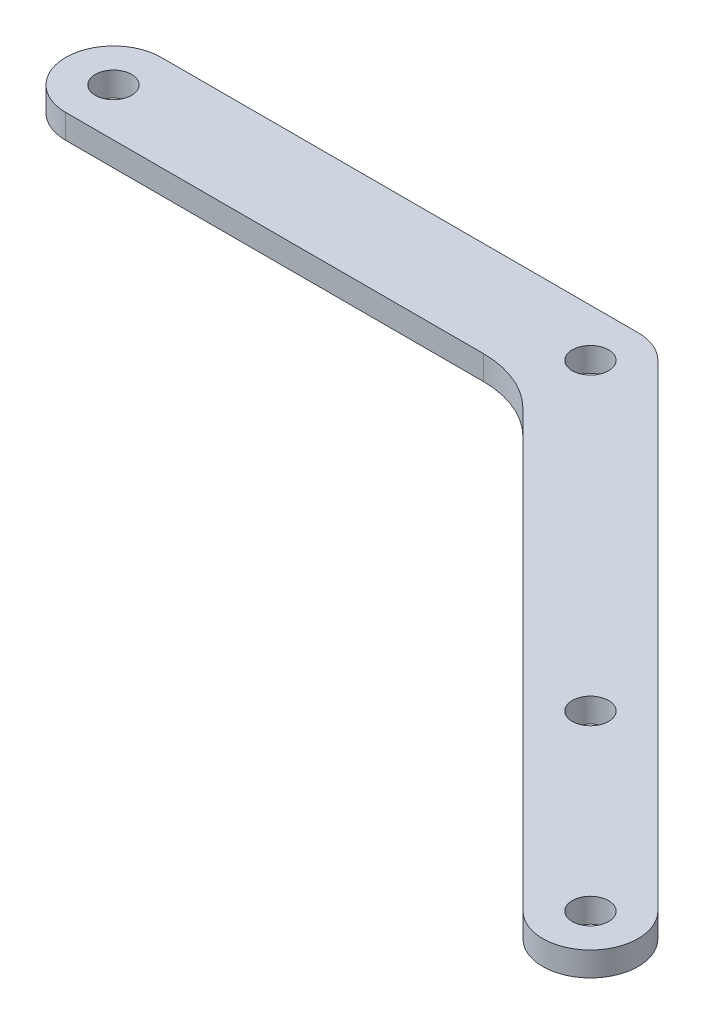
SolidWorks part; units mm, degrees
ref_plane "Front Plane" through (0, 0, 0) normal (0, 0, 1) x (1, 0, 0)
ref_plane "Top Plane" through (0, 0, 0) normal (0, 1, 0) x (1, 0, 0)
ref_plane "Right Plane" through (0, 0, 0) normal (1, 0, 0) x (0, 0, -1)
sketch "Sketch1" plane through (0, 0, 0) normal (0, 1, 0) x (1, 0, 0)
  line L0 (0, 0) -> (-125, 0) construction
  line L1 (0, -12.5) -> (-125, -12.5)
  line L2 (0, 12.5) -> (-125, 12.5)
  line L3 (0, 0) -> (125, -125) construction
  line L4 (8.8388, 8.8388) -> (133.8388, -116.1612)
  line L5 (-8.8388, -8.8388) -> (116.1612, -133.8388)
  line L6 (125, -125) -> (125, 0) construction
  line L7 (125, 0) -> (0, 0) construction
  line L8 (79.583, -79.583) -> (101.8189, -57.3472) construction
  line L9 (101.8189, -57.3472) -> (22.2359, 22.2359) construction
  line L10 (22.2359, 22.2359) -> (0, 0) construction
  arc A0 (0, -12.5) -> (0, 12.5) centre (0, 0) ccw
  arc A1 (-125, 12.5) -> (-125, -12.5) centre (-125, 0) ccw
  arc A2 (8.8388, 8.8388) -> (-8.8388, -8.8388) centre (0, 0) ccw
  arc A3 (116.1612, -133.8388) -> (133.8388, -116.1612) centre (125, -125) ccw
  circle A4 centre (-125, 0) radius 4.7625
  circle A5 centre (0, 0) radius 4.7625
  circle A6 centre (125, -125) radius 4.7625
  circle A7 centre (79.583, -79.583) radius 4.7625
  point P3 (-62.5, 0)
  point P8 (62.5, -62.5)
  dimension "D4" = 9.525
  dimension "D1" = 125
  dimension "D2" = 125
  dimension "D3" = 25
  dimension "D5" = 112.5474
extrude "Boss-Extrude1" add sketch "Sketch1" along normal mid plane 6.35 contours A2 L2 A1 L1 L5 A4 | A0 A2 L5 L1 A5 | L5 A3 L4 A0 L1 A7 A6
fillet "Fillet1" radius 25 1 edges at (-5.1777, 0, 12.5)
